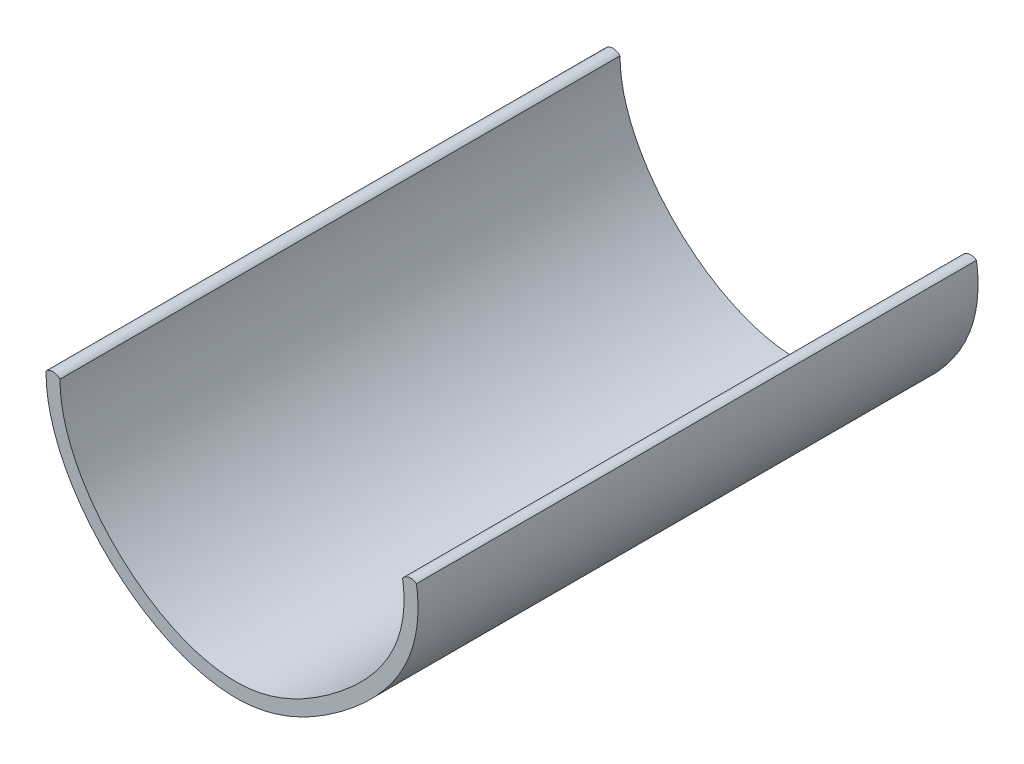
SolidWorks part; units mm, degrees
ref_plane "Front Plane" through (0, 0, 0) normal (0, 0, 1) x (1, 0, 0)
ref_plane "Top Plane" through (0, 0, 0) normal (0, 1, 0) x (1, 0, 0)
ref_plane "Right Plane" through (0, 0, 0) normal (1, 0, 0) x (0, 0, -1)
sketch "Sketch1" plane through (0, 0, 0) normal (0, 0, 1) x (1, 0, 0)
  arc A0 (51.8833, 0.299) -> (47.9283, -0.299) centre (50.2048, -1.9775) ccw construction
  arc A1 (-49.946, -0.0161) -> (-53.9459, 0.0161) centre (-51.9621, -1.9999) ccw construction
  arc A2 (51.8833, 0.299) -> (47.9283, -0.299) centre (50.2048, -1.9775) ccw
  arc A3 (-49.946, -0.0161) -> (-53.9459, 0.0161) centre (-51.9621, -1.9999) ccw
  spline S0 degree 3 poles (3903.8862, -443.5847) (336.7855, 259.1312) (-92.6472, 96.9261) (-48.3186, -22.9477) (-37.4978, -37.6558) (-22.537, -48.289) (-9.353, -52.9781) (-0.8752, -54.0072) (5.8842, -53.4738) (12.4956, -52.0193) (20.4129, -48.7501) (29.2163, -43.1744) (37.2556, -36.6657) (44.2264, -29.1984) (48.6224, -22.0475) (50.983, -15.7278) (52.0925, -10.691) (52.401, -6.2432) (50.3691, 42.2837) (-44.0666, 137.1557) (266.4368, -3992.6053) knots -2.059601 -2.059601 -2.059601 -2.059601 0.0625 0.125 0.25 0.375 0.4375 0.5 0.53125 0.5625 0.625 0.6875 0.75 0.8125 0.875 0.90625 0.9375 0.96875 0.984375 1.760928 1.760928 1.760928 1.760928 only from (-53.9459, 0.0161) to (51.8833, 0.299) construction
  spline S1 degree 3 poles (278.5113, -3992.2704) (-35.4299, 128.1782) (46.6236, 36.2851) (48.3932, -6.1697) (48.1185, -10.1215) (47.1348, -14.588) (45.0312, -20.2258) (41.0485, -26.725) (34.557, -33.6976) (26.8551, -39.936) (18.5288, -45.1982) (9.7645, -48.812) (0.8091, -50.174) (-8.3978, -49.0582) (-20.5646, -44.7473) (-31.8338, -36.7569) (-40.7467, -26.4536) (-45.9062, -17.9297) (-48.6578, -10.476) (-65.4556, 79.4509) (238.6994, 134.4653) (1909.4113, 3482.9937) knots -0.743339 -0.743339 -0.743339 -0.743339 0.015625 0.03125 0.0625 0.09375 0.125 0.1875 0.25 0.3125 0.375 0.4375 0.5 0.5625 0.625 0.75 0.8125 0.875 0.9375 0.96875 2.746973 2.746973 2.746973 2.746973 only from (47.9283, -0.299) to (-49.946, -0.0161) construction
  spline S2 degree 3 poles (-53.9459, 0.0161) (-53.9728, -3.3245) (-53.1169, -9.9721) (-48.3186, -22.9477) (-37.4978, -37.6558) (-22.537, -48.289) (-9.353, -52.9781) (-0.8752, -54.0072) (5.8842, -53.4738) (12.4956, -52.0193) (20.4129, -48.7501) (29.2163, -43.1744) (37.2556, -36.6657) (44.2264, -29.1984) (48.6224, -22.0475) (50.983, -15.7278) (52.0925, -10.691) (52.401, -6.2432) (52.2468, -2.5599) (52.0258, -0.6433) (51.8833, 0.299) knots 0 0 0 0 0.0625 0.125 0.25 0.375 0.4375 0.5 0.53125 0.5625 0.625 0.6875 0.75 0.8125 0.875 0.90625 0.9375 0.96875 0.984375 1 1 1 1
  spline S3 degree 3 poles (47.9283, -0.299) (48.0565, -1.1474) (48.2559, -2.8769) (48.3932, -6.1697) (48.1185, -10.1215) (47.1348, -14.588) (45.0312, -20.2258) (41.0485, -26.725) (34.557, -33.6976) (26.8551, -39.936) (18.5288, -45.1982) (9.7645, -48.812) (0.8091, -50.174) (-8.3978, -49.0582) (-20.5646, -44.7473) (-31.8338, -36.7569) (-40.7467, -26.4536) (-45.9062, -17.9297) (-48.6578, -10.476) (-49.7794, -4.4712) (-49.958, -1.5068) (-49.946, -0.0161) knots 0 0 0 0 0.015625 0.03125 0.0625 0.09375 0.125 0.1875 0.25 0.3125 0.375 0.4375 0.5 0.5625 0.625 0.75 0.8125 0.875 0.9375 0.96875 1 1 1 1
extrude "Boss-Extrude1" add sketch "Sketch1" along normal blind 160
